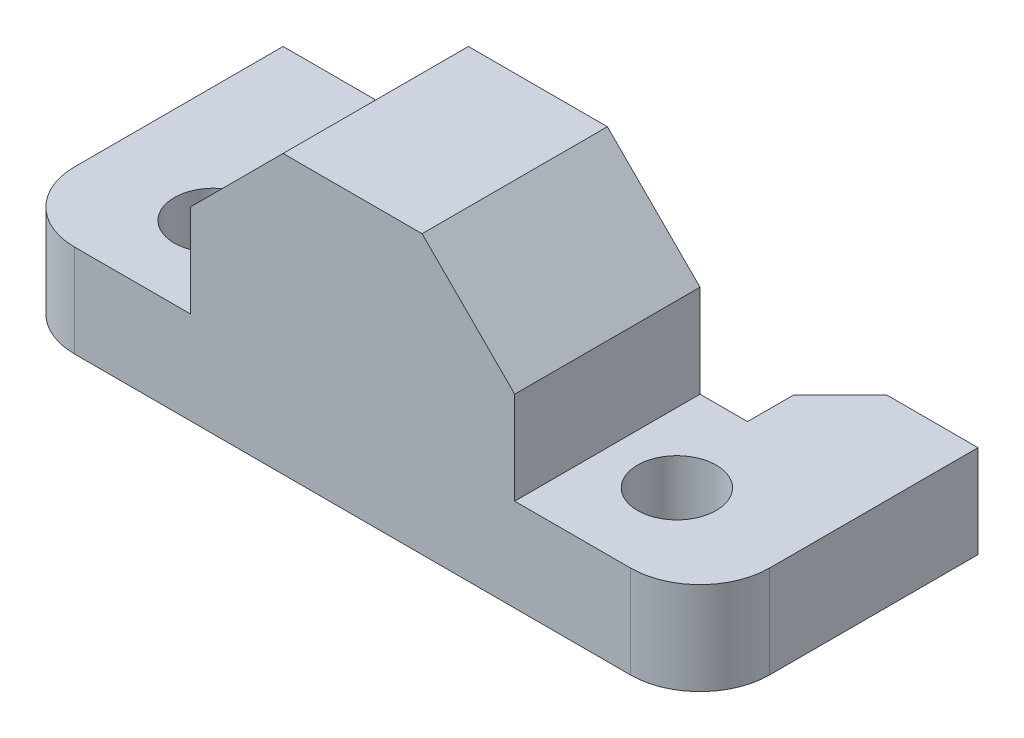
SolidWorks part; units mm, degrees
ref_plane "Front Plane" through (0, 0, 0) normal (0, 0, 1) x (1, 0, 0)
ref_plane "Top Plane" through (0, 0, 0) normal (0, 1, 0) x (1, 0, 0)
ref_plane "Right Plane" through (0, 0, 0) normal (1, 0, 0) x (0, 0, -1)
sketch "Sketch1" plane through (0, 0, 0) normal (0, 1, 0) x (1, 0, 0)
  line L0 (0, 0) -> (20, 0) construction
  line L2 (-5, -4) -> (25, -4)
  line L3 (-5, -4) -> (-5, 4)
  line L4 (-5, 4) -> (25, 4)
  line L5 (25, -4) -> (25, 4)
  line L6 (-5, -4) -> (25, 4) construction
  line L7 (-5, 4) -> (25, -4) construction
  circle A0 centre (0, 0) radius 1.7
  circle A1 centre (20, 0) radius 1.7
  point P5 (10, 0)
extrude "Boss-Extrude1" add sketch "Sketch1" along normal blind 4
fillet "Fillet1" radius 3 2 edges at (25, 2, 4) (-5, 2, 4)
sketch "Sketch2" plane through (0, 4, 0) normal (0, 1, 0) x (1, 0, 0)
  line L0 (10, 4) -> (19.05, 4)
  line L1 (25, 4) -> (-5, 4) construction
  line L2 (19.05, 4) -> (25, 4)
  line L3 (25, 4) -> (25, 8)
  line L4 (25, 8) -> (19.05, 8)
  line L5 (19.05, 8) -> (19.05, 4)
  line L6 (10, -4) -> (10, -12.514)
  line L7 (-2, -4) -> (22, -4) construction
  line L8 (0.95, 8) -> (0.95, 4)
  line L9 (-5, 8) -> (0.95, 8)
  line L10 (-5, 4) -> (-5, 8)
  line L11 (0.95, 4) -> (-5, 4)
  line M6 (25, 4) -> (-5, 4)
extrude "Boss-Extrude2" add sketch "Sketch2" against normal blind 4 contours L10 L8 L9 M6 | L4 L5 L3 M6
sketch "Sketch3" plane through (0, 4, 0) normal (0, 1, 0) x (1, 0, 0)
  line L1 (-5, 8) -> (-5, -1) construction
  line L5 (10, 4) -> (10, -4) construction
  line L6 (17, 4) -> (3, 4)
  line L7 (19.05, 4) -> (0.95, 4) construction
  line L8 (3, 4) -> (3, -4)
  line L9 (-2, -4) -> (22, -4) construction
  line L10 (3, -4) -> (17, -4)
  line L11 (17, 4) -> (17, -4)
  dimension "D1" = 15
extrude "Boss-Extrude3" add sketch "Sketch3" along normal blind 8
chamfer "Chamfer1" distance 4 angle 45 2 edges at (17, 12, 0) (3, 12, 0)
chamfer "Chamfer2" distance 2 angle 45 2 edges at (19.05, 2, -8) (0.95, 2, -8)
